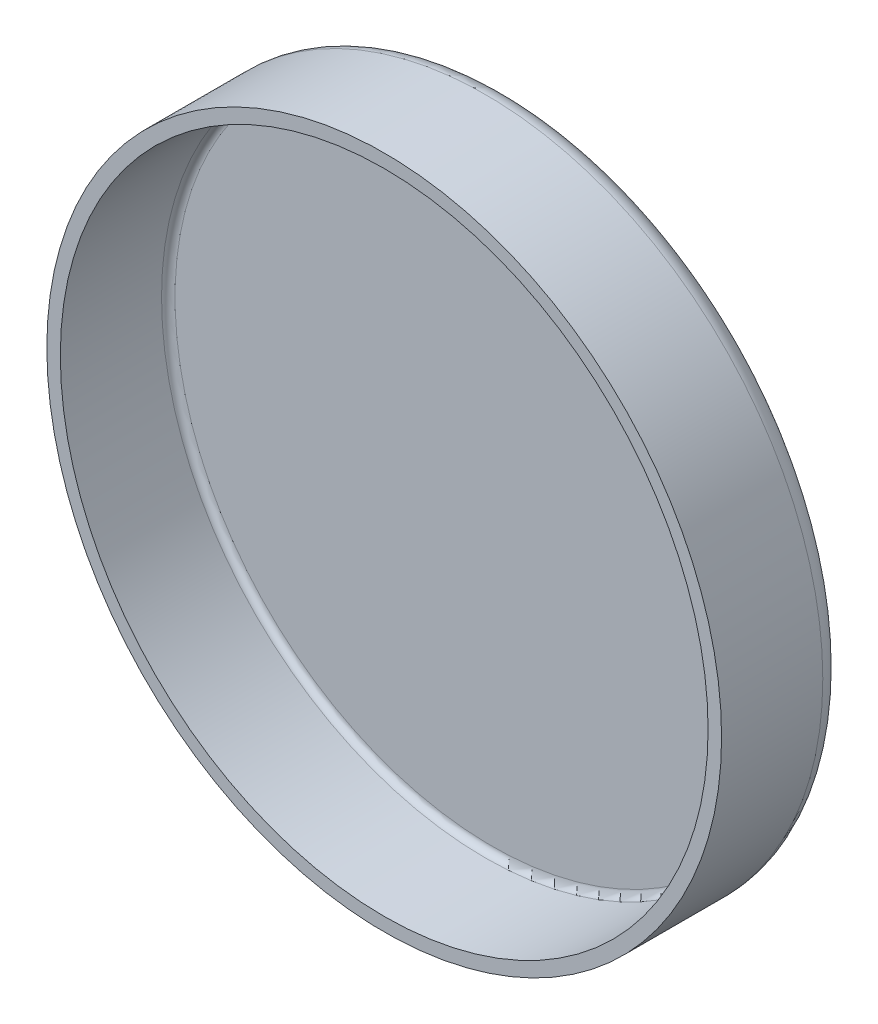
SolidWorks part; units mm, degrees
material "1.4301 (X5CrNi18-10)"
ref_plane "Front Plane" through (0, 0, 0) normal (0, 0, 1) x (1, 0, 0)
ref_plane "Top Plane" through (0, 0, 0) normal (0, 1, 0) x (1, 0, 0)
ref_plane "Right Plane" through (0, 0, 0) normal (1, 0, 0) x (0, 0, -1)
sketch "Sketch1" plane through (0, 0, 0) normal (0, 0, 1) x (1, 0, 0)
  circle A0 centre (0, 0) radius 25
  dimension "D1" = 50
extrude "Boss-Extrude1" add sketch "Sketch1" along normal blind 9
shell "Shell1" thickness 1
fillet "Fillet1" radius 0.5 1 edges at (24, 0, 1)
fillet "Fillet2" radius 1.5 1 edges at (25, 0, 0)
